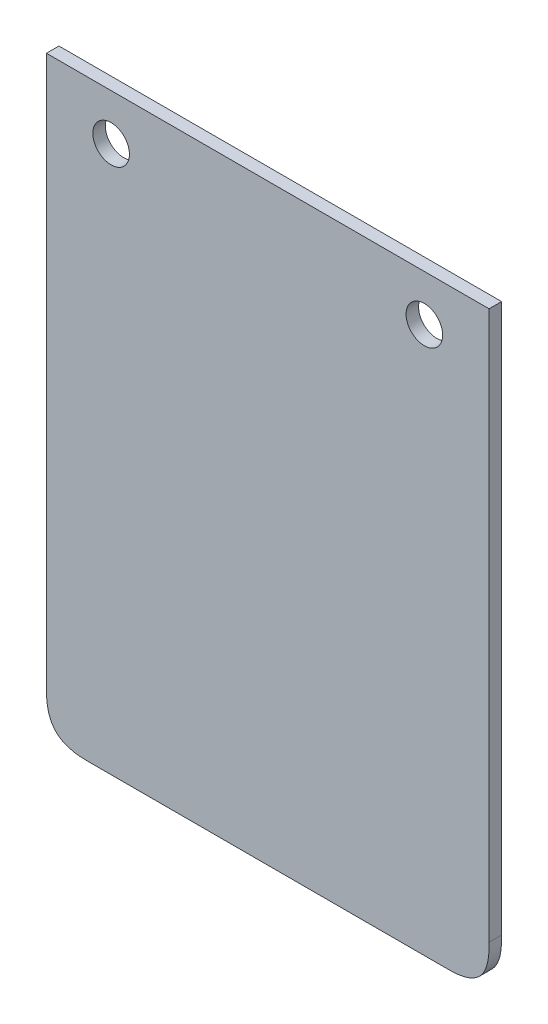
SolidWorks part; units mm, degrees
ref_plane "前视基准面" through (0, 0, 0) normal (0, 0, 1) x (1, 0, 0)
ref_plane "上视基准面" through (0, 0, 0) normal (0, 1, 0) x (1, 0, 0)
ref_plane "右视基准面" through (0, 0, 0) normal (1, 0, 0) x (0, 0, -1)
sketch "草图1" plane through (0, 0, 0) normal (0, 0, 1) x (1, 0, 0)
  line L4 (-14.1692, -23.6512) -> (14.1692, -23.6512)
  line L5 (17.6692, -20.1512) -> (17.6692, 23.6512)
  line L6 (17.6692, 23.6512) -> (-17.6692, 23.6512)
  line L7 (-17.6692, 23.6512) -> (-17.6692, -20.1512)
  line L8 (-14.1692, -23.6512) -> (14.1692, -23.6512)
  line L9 (17.6692, -20.1512) -> (17.6692, 23.6512)
  line L10 (17.6692, 23.6512) -> (-17.6692, 23.6512)
  line L11 (-17.6692, 23.6512) -> (-17.6692, -20.1512)
  spline S2 degree 2 poles (274.2006, 3969.0885) (-19.8588, 13.301) (-17.6527, -20.8777) (-17.6275, -21.269) (-17.5547, -21.5967) (-17.3748, -22.4058) (-16.903, -22.8797) (-16.4309, -23.3539) (-15.6196, -23.5356) (-15.2927, -23.6088) (-14.9001, -23.6345) (19.2195, -25.8673) (3974.9411, 270.0408) knots -16.661779 -16.661779 -16.661779 0.125 0.125 0.25 0.25 0.5 0.5 0.75 0.75 0.875 0.875 17.566418 17.566418 17.566418 only from (-17.6692, -20.1512) to (-14.1692, -23.6512)
  spline S3 degree 2 poles (-3975.0706, 268.2185) (-19.2831, -25.8409) (14.8956, -23.6348) (15.2869, -23.6096) (15.6146, -23.5367) (16.4237, -23.3569) (16.8976, -22.8851) (17.3718, -22.413) (17.5535, -21.6017) (17.6268, -21.2747) (17.6524, -20.8822) (19.8852, 13.2374) (-276.0229, 3968.959) knots -16.661779 -16.661779 -16.661779 0.125 0.125 0.25 0.25 0.5 0.5 0.75 0.75 0.875 0.875 17.566418 17.566418 17.566418 only from (14.1692, -23.6512) to (17.6692, -20.1512)
  spline S4 degree 2 poles (-17.6692, -20.1512) (-17.6692, -20.6232) (-17.6527, -20.8777) (-17.6275, -21.269) (-17.5547, -21.5967) (-17.3748, -22.4058) (-16.903, -22.8797) (-16.4309, -23.3539) (-15.6196, -23.5356) (-15.2927, -23.6088) (-14.9001, -23.6345) (-14.6446, -23.6512) (-14.1692, -23.6512) knots 0 0 0 0.125 0.125 0.25 0.25 0.5 0.5 0.75 0.75 0.875 0.875 1 1 1
  spline S5 degree 2 poles (14.1692, -23.6512) (14.6411, -23.6512) (14.8956, -23.6348) (15.2869, -23.6096) (15.6146, -23.5367) (16.4237, -23.3569) (16.8976, -22.8851) (17.3718, -22.413) (17.5535, -21.6017) (17.6268, -21.2747) (17.6524, -20.8822) (17.6692, -20.6267) (17.6692, -20.1512) knots 0 0 0 0.125 0.125 0.25 0.25 0.5 0.5 0.75 0.75 0.875 0.875 1 1 1
  dimension "D1" = 0
extrude "凸台-拉伸1" add sketch "草图1" along normal blind 1
sketch "草图3" plane through (0, 0, 1) normal (0, 0, 1) x (1, 0, 0)
  circle A0 centre (-12.5034, 19.975) radius 1.4613 construction
  circle A1 centre (-12.5034, 19.975) radius 1.4613
extrude "切除-拉伸1" cut sketch "草图3" against normal through all
sketch "草图4" plane through (0, 0, 1) normal (0, 0, 1) x (1, 0, 0)
  circle A0 centre (12.5034, 19.975) radius 1.4613 construction
  circle A1 centre (12.5034, 19.975) radius 1.4613
extrude "切除-拉伸2" cut sketch "草图4" against normal through all
